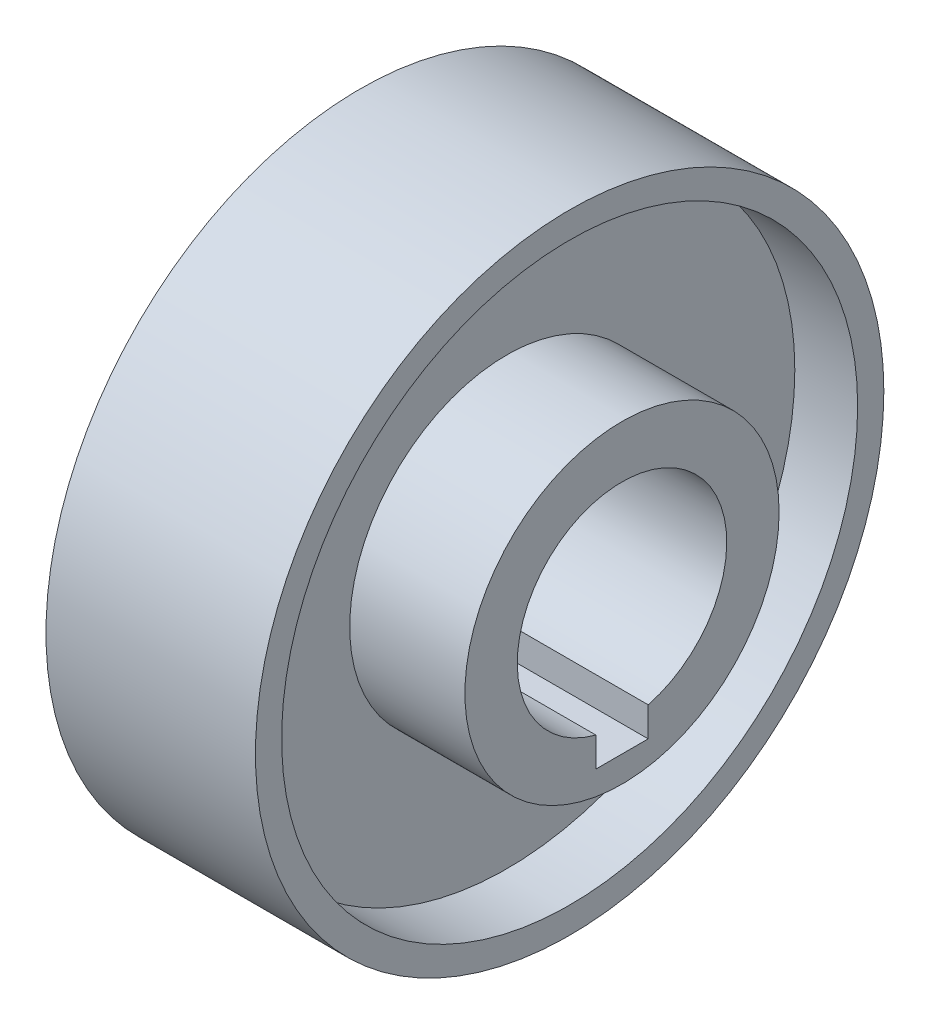
SolidWorks part; units mm, degrees
ref_plane "Ön Düzlem" through (0, 0, 0) normal (0, 0, 1) x (1, 0, 0)
ref_plane "Üst Düzlem" through (0, 0, 0) normal (0, 1, 0) x (1, 0, 0)
ref_plane "Sağ Düzlem" through (0, 0, 0) normal (1, 0, 0) x (0, 0, -1)
sketch "Çizim1" plane through (0, 0, 0) normal (1, 0, 0) x (0, 0, -1)
  line L0 (0, 0) -> (0, -125) construction
  line L1 (-25, -125) -> (25, -125)
  line L2 (25, -125) -> (25, -96.8246)
  line L3 (-25, -125) -> (-25, -96.8246)
  circle A0 centre (0, 0) radius 150
  arc A1 (25, -96.8246) -> (-25, -96.8246) centre (0, 0) ccw
  dimension "D1" = 300
  dimension "D2" = 200
  dimension "D3" = 125
  dimension "D4" = 25
extrude "Yükseklik-Ekstrüzyon1" add sketch "Çizim1" along normal mid plane 300
sketch "Çizim2" plane through (0, 0, 0) normal (1, 0, 0) x (0, 0, -1)
  circle A0 centre (0, 0) radius 300
  circle A1 centre (0, 0) radius 275
  dimension "D1" = 600
  dimension "D2" = 550
extrude "Yükseklik-Ekstrüzyon2" add sketch "Çizim2" along normal mid plane 200 separate body
sketch "Çizim3" plane through (0, 0, 0) normal (1, 0, 0) x (0, 0, -1)
  circle A0 centre (0, 0) radius 275 construction
  circle A1 centre (0, 0) radius 150 construction
  circle A2 centre (0, 0) radius 275
  circle A3 centre (0, 0) radius 150
extrude "Yükseklik-Ekstrüzyon3" add sketch "Çizim3" along normal mid plane 80
